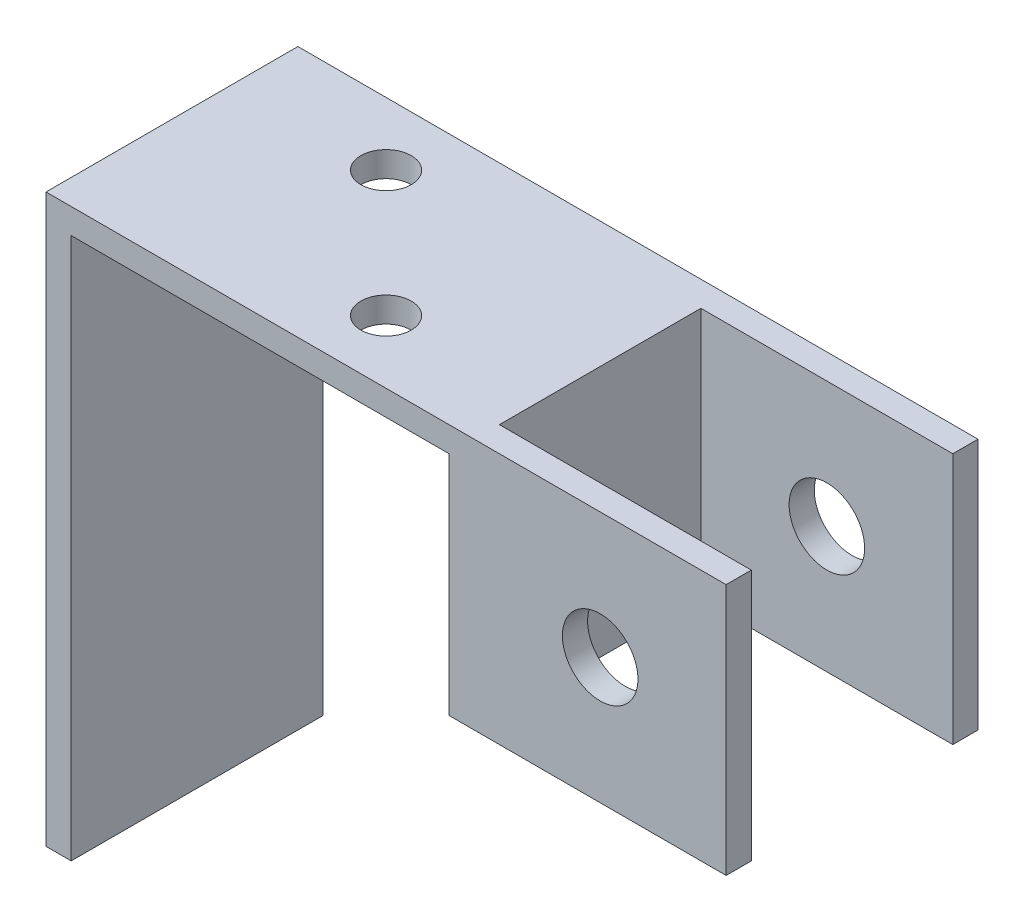
SolidWorks part; units mm, degrees
ref_plane "Front Plane" through (0, 0, 0) normal (0, 0, 1) x (1, 0, 0)
ref_plane "Top Plane" through (0, 0, 0) normal (0, 1, 0) x (1, 0, 0)
ref_plane "Right Plane" through (0, 0, 0) normal (1, 0, 0) x (0, 0, -1)
sketch "Sketch1" plane through (0, 0, 0) normal (0, 0, 1) x (1, 0, 0)
  line L0 (-8.2963, 12.1852) -> (-8.2963, -32.8148)
  line L1 (-8.2963, -32.8148) -> (-6.2963, -32.8148)
  line L2 (-6.2963, -32.8148) -> (-6.2963, 10.1852)
  line L3 (-6.2963, 10.1852) -> (23.7037, 10.1852)
  line L4 (23.7037, 10.1852) -> (23.7037, -7.8148)
  line L5 (23.7037, -7.8148) -> (25.7037, -7.8148)
  line L6 (25.7037, -7.8148) -> (25.7037, 12.1852)
  line L7 (25.7037, 12.1852) -> (-8.2963, 12.1852)
  dimension "D1" = 2
  dimension "D2" = 2
  dimension "D3" = 2
  dimension "D4" = 30
  dimension "D5" = 20
  dimension "D6" = 45
extrude "Boss-Extrude1" add sketch "Sketch1" along normal blind 20
sketch "Sketch2" plane through (0, 12.1852, 0) normal (0, 1, 0) x (1, 0, 0)
  line L0 (-1.3581, -10) -> (14.0148, -10) construction
  line L1 (-8.2963, -20) -> (-8.2963, 0) construction
  circle A0 centre (13.7037, -15) radius 2
  circle A1 centre (3.7037, -5) radius 2
  dimension "D5" = 4
  dimension "D6" = 4
  dimension "D1" = 5
  dimension "D2" = 5
  dimension "D3" = 10
  dimension "D4" = 12
extrude "Cut-Extrude1" cut sketch "Sketch2" against normal blind 20
sketch "Sketch3" plane through (25.7037, 0, 0) normal (1, 0, 0) x (0, 0, -1)
  line L0 (-20, -7.8148) -> (0, -7.8148) construction
  line L1 (-20, 12.1852) -> (-18, 12.1852)
  line L2 (-20, 12.1852) -> (-20, -7.8148)
  line L3 (-20, -7.8148) -> (-18, -7.8148)
  line L4 (-18, 12.1852) -> (-18, -7.8148)
  line L5 (-10, 12.1852) -> (-10, -3.4067) construction
  line L6 (-20, 12.1852) -> (0, 12.1852) construction
  line L7 (0, -7.8148) -> (-2, -7.8148)
  line L8 (-2, 12.1852) -> (-2, -7.8148)
  line L9 (0, 12.1852) -> (-2, 12.1852)
  line L10 (0, 12.1852) -> (0, -7.8148)
  dimension "D1" = 2
extrude "Boss-Extrude2" add sketch "Sketch3" along normal blind 20
sketch "Sketch4" plane through (0, 0, 0) normal (0, 0, -1) x (-1, 0, 0)
  line L0 (-45.7037, -7.8148) -> (-45.7037, 12.1852) construction
  circle A0 centre (-35.7037, 2.1852) radius 3
  dimension "D2" = 6
  dimension "D1" = 10
extrude "Cut-Extrude2" cut sketch "Sketch4" against normal through all both and the other way through all
